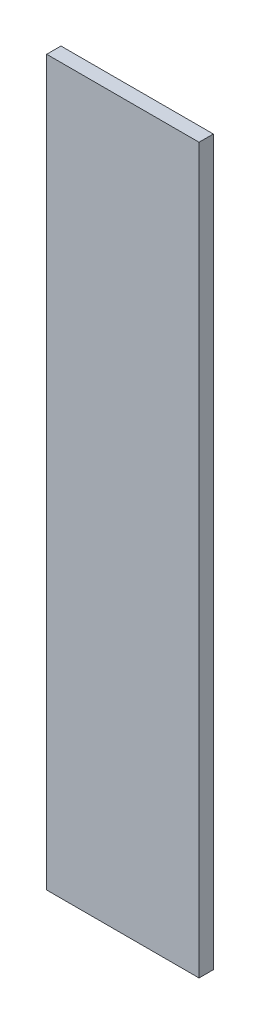
SolidWorks part; units mm, degrees
ref_plane "Płaszczyzna przednia" through (0, 0, 0) normal (0, 0, 1) x (1, 0, 0)
ref_plane "Płaszczyzna górna" through (0, 0, 0) normal (0, 1, 0) x (1, 0, 0)
ref_plane "Płaszczyzna prawa" through (0, 0, 0) normal (1, 0, 0) x (0, 0, -1)
sketch "Szkic1" plane through (0, 0, 0) normal (0, 0, 1) x (1, 0, 0)
  line L1 (0, 0) -> (320, 0)
  line L2 (0, 0) -> (0, 1520)
  line L3 (0, 1520) -> (320, 1520)
  line L4 (320, 0) -> (320, 1520)
  dimension "D1" = 1520
  dimension "D2" = 320
extrude "Dodanie-wyciągnięcie1" add sketch "Szkic1" along normal blind 30
ref_plane "Płaszczyzna1" through (0, 760, 0) normal (0, -1, 0) x (-1, 0, 0)
